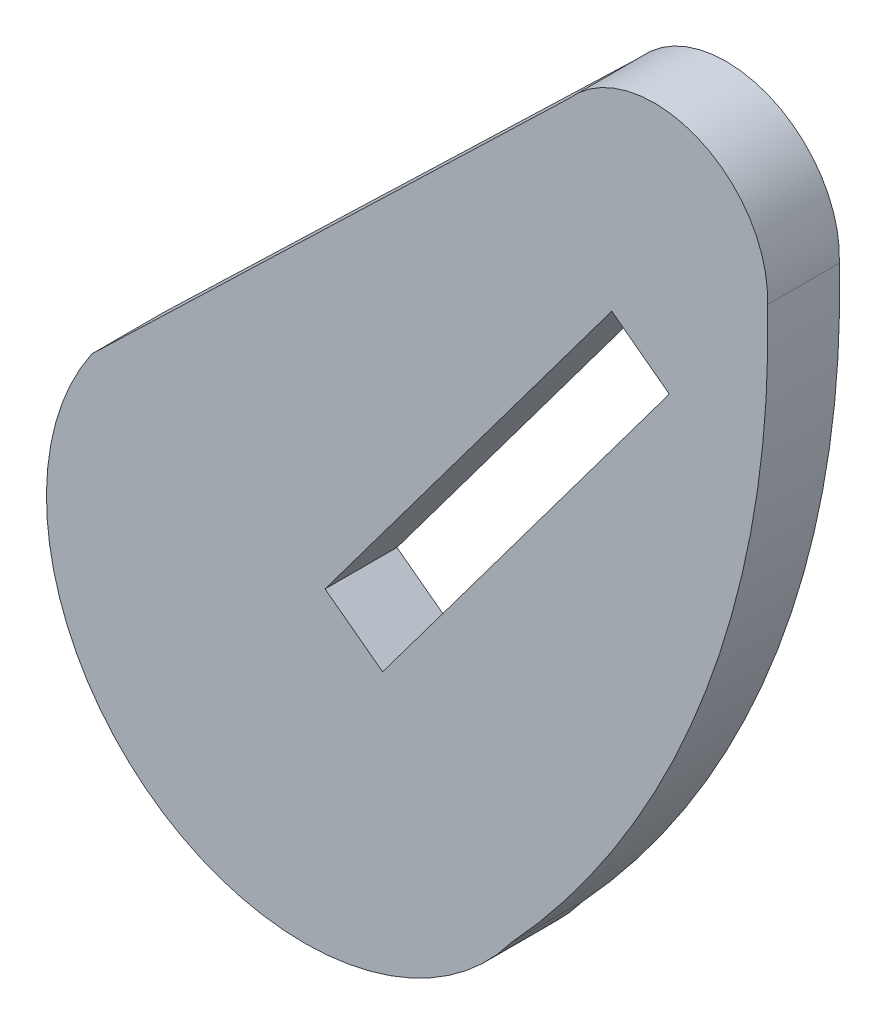
SolidWorks part; units mm, degrees
ref_plane "Front" through (0, 0, 0) normal (0, 0, 1) x (1, 0, 0)
ref_plane "Top" through (0, 0, 0) normal (0, 1, 0) x (1, 0, 0)
ref_plane "Right" through (0, 0, 0) normal (1, 0, 0) x (0, 0, -1)
sketch "Sketch1" plane through (0, 0, 0) normal (0, 0, 1) x (1, 0, 0)
  line L0 (-809.5317, -111.2297) -> (-789.6141, -92.0396)
  line L1 (-797.3908, -116.6544) -> (-785.4232, -100.6301)
  line L2 (-785.4232, -100.6301) -> (-787.8269, -98.835)
  line L3 (-787.8269, -98.835) -> (-799.7944, -114.8592)
  line L4 (-799.7944, -114.8592) -> (-797.3908, -116.6544)
  arc A0 (-809.5317, -111.2297) -> (-792.0316, -123.7697) centre (-800.658, -117.3272) ccw
  arc A1 (-792.0316, -123.7697) -> (-781.3261, -95.3477) centre (-821.6456, -96.388) ccw
  arc A2 (-781.3261, -95.3477) -> (-789.6141, -92.0396) centre (-786.0479, -95.1411) ccw
  dimension "D1" = 3
  dimension "D2" = 20
extrude "Base-Extrude" add sketch "Sketch1" along normal blind 3
